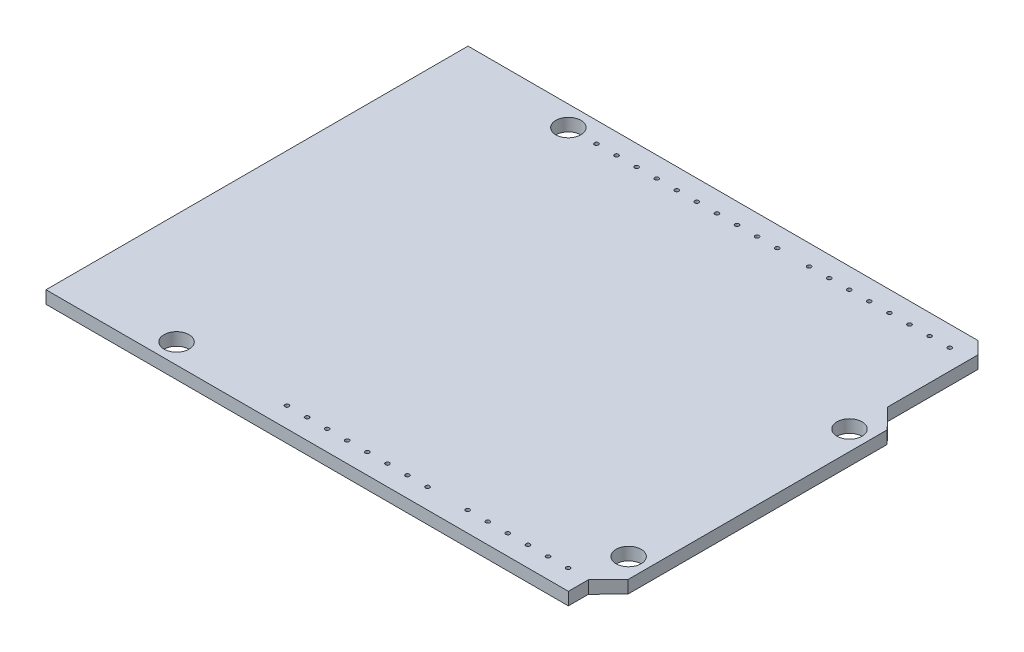
SolidWorks part; units mm, degrees
ref_plane "Alzado" through (0, 0, 0) normal (0, 0, 1) x (1, 0, 0)
ref_plane "Planta" through (0, 0, 0) normal (0, 1, 0) x (1, 0, 0)
ref_plane "Vista lateral" through (0, 0, 0) normal (1, 0, 0) x (0, 0, -1)
sketch "Board" plane through (0, 0, 0) normal (0, 1, 0) x (1, 0, 0)
  line L0 (68.55, 37.846) -> (68.55, 5.08)
  line L1 (66.07, 0) -> (0, 0)
  line L2 (66.07, 51.8137) -> (66.07, 40.386)
  line L3 (66.07, 0) -> (66.07, 2.54)
  line L4 (66.07, 40.386) -> (68.55, 37.846)
  line L5 (68.55, 5.08) -> (66.07, 2.54)
  line L6 (0, 0) -> (0, 53.3785)
  line L7 (64.5052, 53.3785) -> (0, 53.3785)
  line L8 (66.07, 51.8137) -> (64.5052, 53.3785)
sketch "Drills" plane through (0, 0, 0) normal (0, 1, 0) x (1, 0, 0)
  line L0 (13.97, 2.54) -> (63.5, 2.54) construction
  line L2 (15.27, 50.8) -> (63.5, 50.8) construction
  circle A0 centre (15.27, 50.8) radius 1.5875
  circle A1 centre (66.07, 35.56) radius 1.5875
  circle A2 centre (66.07, 7.62) radius 1.5875
  circle A3 centre (13.97, 2.54) radius 1.5875
sketch "Pinout" plane through (0, 0, 0) normal (0, 1, 0) x (1, 0, 0)
  circle A0 centre (63.5, 2.54) radius 0.254
  circle A1 centre (60.96, 2.54) radius 0.254
  circle A2 centre (58.42, 2.54) radius 0.254
  circle A3 centre (55.88, 2.54) radius 0.254
  circle A4 centre (53.34, 2.54) radius 0.254
  circle A5 centre (50.8, 2.54) radius 0.254
  circle A6 centre (45.72, 2.54) radius 0.254
  circle A7 centre (43.18, 2.54) radius 0.254
  circle A8 centre (40.64, 2.54) radius 0.254
  circle A9 centre (38.1, 2.54) radius 0.254
  circle A10 centre (35.56, 2.54) radius 0.254
  circle A11 centre (33.02, 2.54) radius 0.254
  circle A12 centre (30.48, 2.54) radius 0.254
  circle A13 centre (27.94, 2.54) radius 0.254
  circle A14 centre (63.5, 50.8) radius 0.254
  circle A15 centre (60.96, 50.8) radius 0.254
  circle A16 centre (58.42, 50.8) radius 0.254
  circle A17 centre (55.88, 50.8) radius 0.254
  circle A18 centre (53.34, 50.8) radius 0.254
  circle A19 centre (50.8, 50.8) radius 0.254
  circle A20 centre (48.26, 50.8) radius 0.254
  circle A21 centre (45.72, 50.8) radius 0.254
  circle A22 centre (41.686, 50.8) radius 0.254
  circle A23 centre (39.146, 50.8) radius 0.254
  circle A24 centre (36.606, 50.8) radius 0.254
  circle A25 centre (34.066, 50.8) radius 0.254
  circle A26 centre (31.526, 50.8) radius 0.254
  circle A27 centre (28.986, 50.8) radius 0.254
  circle A28 centre (26.446, 50.8) radius 0.254
  circle A29 centre (23.906, 50.8) radius 0.254
  circle A30 centre (21.366, 50.8) radius 0.254
  circle A31 centre (18.826, 50.8) radius 0.254
  dimension "D1" = 8
  dimension "D2" = 10
  dimension "D3" = 6
  dimension "D4" = 8
extrude "Saliente-Extruir1" add sketch "Board" along normal blind 1.6002
extrude "Cortar-Extruir1" cut sketch "Drills" along normal blind 1.6002
extrude "Cortar-Extruir2" cut sketch "Pinout" along normal blind 1.6002
